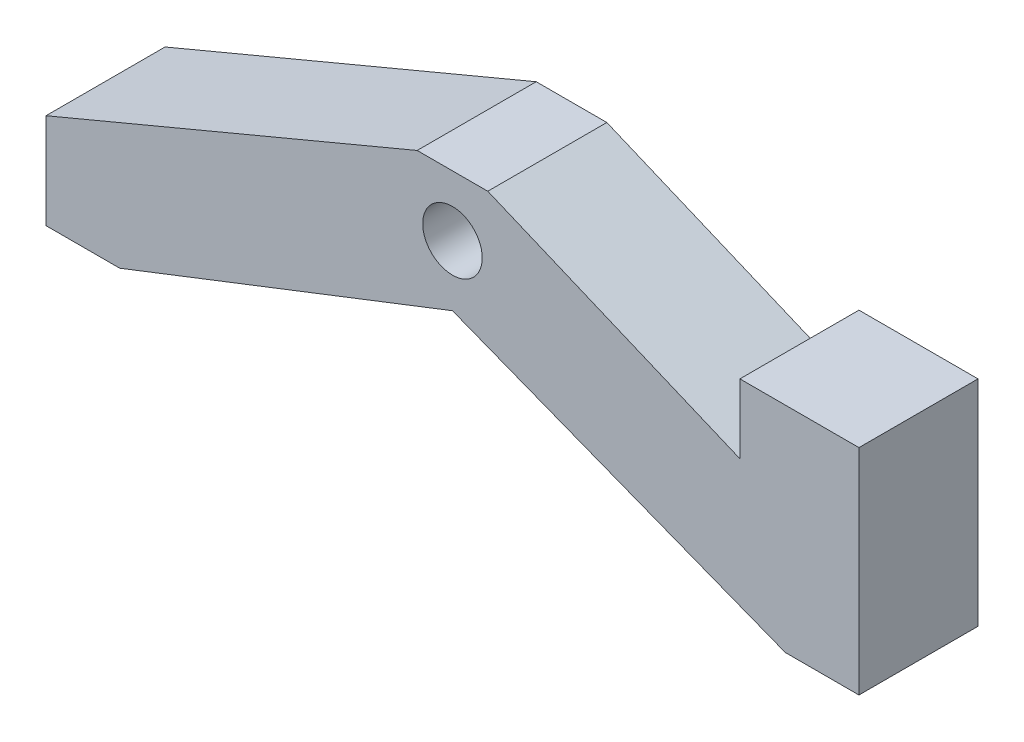
SolidWorks part; units mm, degrees
material "Cast Stainless Steel"
ref_plane "Front Plane" through (0, 0, 0) normal (0, 0, 1) x (1, 0, 0)
ref_plane "Top Plane" through (0, 0, 0) normal (0, 1, 0) x (1, 0, 0)
ref_plane "Right Plane" through (0, 0, 0) normal (1, 0, 0) x (0, 0, -1)
sketch "Sketch1" plane through (0, 0, 0) normal (0, 0, 1) x (1, 0, 0)
  line L0 (0, 0) -> (27.956, -10.8841)
  line L1 (27.956, -10.8841) -> (34.1439, -10.8841)
  line L2 (34.1439, -10.8841) -> (34.1439, -2.8841)
  line L3 (34.1439, -2.8841) -> (2.9662, 10.1768)
  line L4 (2.9662, 10.1768) -> (-2.9662, 10.1768)
  line L5 (0, 0) -> (0, 10.1768) construction
  line L6 (-34.1439, -2.8841) -> (-2.9662, 10.1768)
  line L7 (-34.1439, -10.8841) -> (-34.1439, -2.8841)
  line L8 (-27.956, -10.8841) -> (-34.1439, -10.8841)
  line L9 (0, 0) -> (-27.956, -10.8841)
  circle A0 centre (0, 5.0884) radius 2.5
  dimension "D4" = 5
  dimension "D1" = 30
  dimension "D2" = 8
  dimension "D3" = 6.1879
extrude "Boss-Extrude1" add sketch "Sketch1" along normal mid plane 10 contours L4 L6 L7 L8 L9 L0 L1 L2 L3 | A0
sketch "Sketch3" plane through (0, 0, 5) normal (0, 0, 1) x (1, 0, 0)
  line L0 (34.1439, -2.8841) -> (24.1439, 1.3051)
  line L1 (34.1439, -2.8841) -> (2.9662, 10.1768) construction
  line L2 (24.1439, 1.3051) -> (24.1439, 7.1159)
  line L3 (24.1439, 7.1159) -> (34.1439, 7.1159)
  line L4 (34.1439, 7.1159) -> (34.1439, -2.8841)
  dimension "D1" = 10
  dimension "D2" = 10
extrude "Boss-Extrude2" add sketch "Sketch3" against normal blind 10
